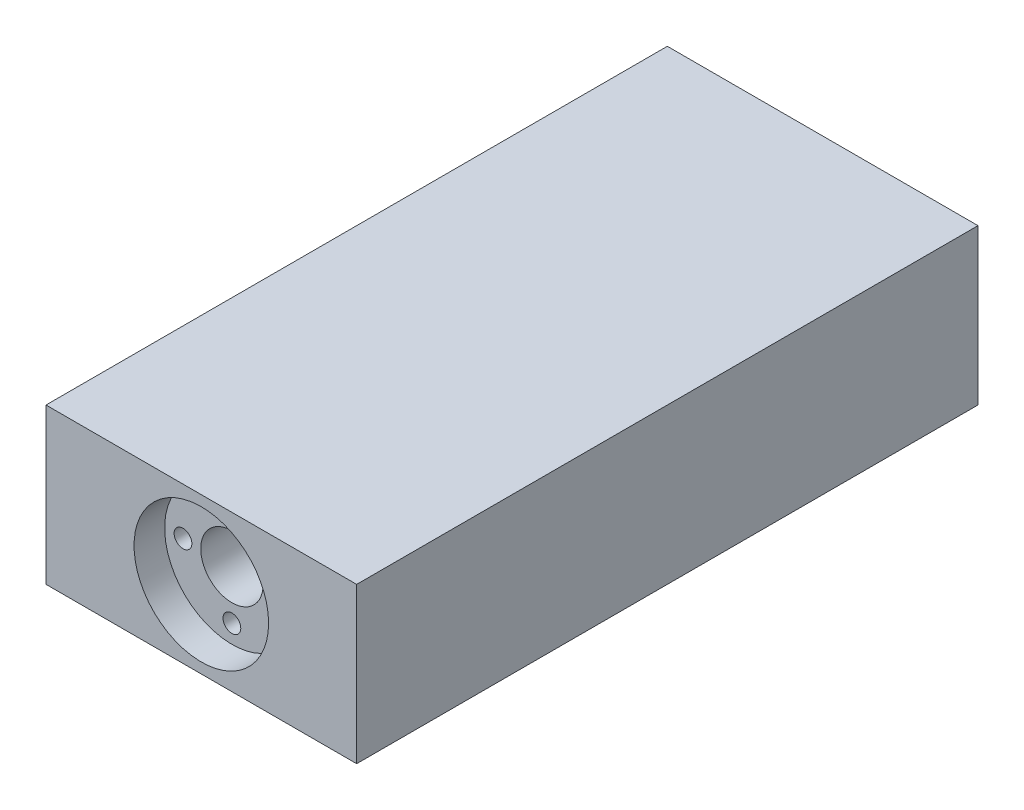
SolidWorks part; units mm, degrees
ref_plane "Front Plane" through (0, 0, 0) normal (0, 0, 1) x (1, 0, 0)
ref_plane "Top Plane" through (0, 0, 0) normal (0, 1, 0) x (1, 0, 0)
ref_plane "Right Plane" through (0, 0, 0) normal (1, 0, 0) x (0, 0, -1)
sketch "Sketch1" plane through (0, 0, 0) normal (0, 0, 1) x (1, 0, 0)
  line L1 (0, 0) -> (50.8, 0)
  line L2 (0, 0) -> (0, 25.4)
  line L3 (0, 25.4) -> (50.8, 25.4)
  line L4 (50.8, 0) -> (50.8, 25.4)
  dimension "D1" = 50.8
  dimension "D2" = 25.4
extrude "base" add sketch "Sketch1" along normal blind 101.6
sketch "Sketch2" plane through (0, 0, 101.6) normal (0, 0, 1) x (1, 0, 0)
  line L0 (0, 25.4) -> (50.8, 0) construction
  line L1 (50.8, 25.4) -> (0, 0) construction
  circle A0 centre (25.4, 12.7) radius 11
  dimension "D1" = 22
extrude "leadnut_flange_inset" cut sketch "Sketch2" against normal blind 5
sketch "Sketch3" plane through (0, 0, 96.6) normal (0, 0, 1) x (1, 0, 0)
  circle A0 centre (25.4, 12.7) radius 5.1
  circle A1 centre (25.4, 12.7) radius 11 construction
  dimension "D1" = 10.2
extrude "leadnut_through_hole" cut sketch "Sketch3" against normal through all
hole_wizard "leadnut_hole_pattern" positions "Sketch5" profile "Sketch4" tap size "M3.5x0.6" standard "ANSI Metric"
sketch "Sketch5" plane through (0, 0, 96.6) normal (0, 0, 1) x (1, 0, 0)
  line L1 (17.4, 20.7) -> (33.4, 20.7)
  line L2 (17.4, 20.7) -> (17.4, 4.7)
  line L3 (17.4, 4.7) -> (33.4, 4.7)
  line L4 (33.4, 20.7) -> (33.4, 4.7)
  line L5 (17.4, 20.7) -> (33.4, 4.7) construction
  line L6 (17.4, 4.7) -> (33.4, 20.7) construction
  point P1 (25.4, 12.7)
  point P109 (25.4, 20.7)
  point P111 (17.4, 12.7)
  point P113 (25.4, 4.7)
  point P115 (33.4, 12.7)
  dimension "D1" = 16
cosmetic thread "Hole Thread1" parameters "D1"=3.048, "D2"=3.5
cosmetic thread "Hole Thread2" parameters "D1"=3.048, "D2"=3.5
cosmetic thread "Hole Thread3" parameters "D1"=3.048, "D2"=3.5
cosmetic thread "Hole Thread4" parameters "D1"=3.048, "D2"=3.5
sketch "Sketch4" plane through (25.4, 12.7, 96.6) normal (1, 0, 0) x (0, -1, 0)
  line L0 (0, 0) -> (0, 10.8713)
  line L1 (0, 10.8713) -> (1.45, 10)
  line L2 (1.45, 10) -> (1.45, 0)
  line L5 (1.45, 0) -> (0, 0)
  line L10 (0, 10.8713) -> (-1.45, 10) construction
  line L11 (0, -6.35) -> (0, 107.95) construction
  dimension "Tap Drill Dia." = 2.9
  dimension "Tap Drill Depth" = 10
  dimension "Drill Angle" = 118
equation "\"baseplate_thickness\"=0.47"
equation "\"baseplate_length\"= 12"
equation "\"baseplate_width\"= 4"
equation "\"rail_width\"= 1"
equation "\"rail_radial_clearance\"= 0.25"
equation "\"slider_width\"= 2"
equation "\"slider_length\"= 4"
equation "\"slider_thickness\"= 1"
equation "\"side_radial_clearance\"= 0.01"
equation "\"front_radial_clearance\"= 0.01"
equation "\"side_plate_width\"= (\"baseplate_width\" - \"slider_width\" - ( 2 * \"side_radial_clearance\" ))/2"
equation "\"side_plate_height\"= \"slider_thickness\" + ( 2 * \"front_radial_clearance\" )"
equation "\"keeper_plate_thickness\"= 0.5"
equation "\"keeper_plate_width\"= (\"baseplate_width\" - \"rail_width\" -  2 * \"rail_radial_clearance\")/2"
equation "\"D1@Sketch1\"=\"slider_width\""
equation "\"D2@Sketch1\"=\"slider_thickness\""
equation "\"D1@base\" = \"slider_length\""
equation "\"leadnut_flange_diam\"= 22mm"
equation "\"D1@Sketch2\"=\"leadnut_flange_diam\""
equation "\"leadnut_flange_depth\"= 5mm"
equation "\"D1@leadnut_flange_inset\" = \"leadnut_flange_depth\""
equation "\"leadnut_shoulder_diam\"= 10.2mm"
equation "\"D1@Sketch3\"=\"leadnut_shoulder_diam\""
equation "\"leadnut_hole_pattern_diam\"=0.629921"
equation "\"D1@Sketch5\"=\"leadnut_hole_pattern_diam\""
